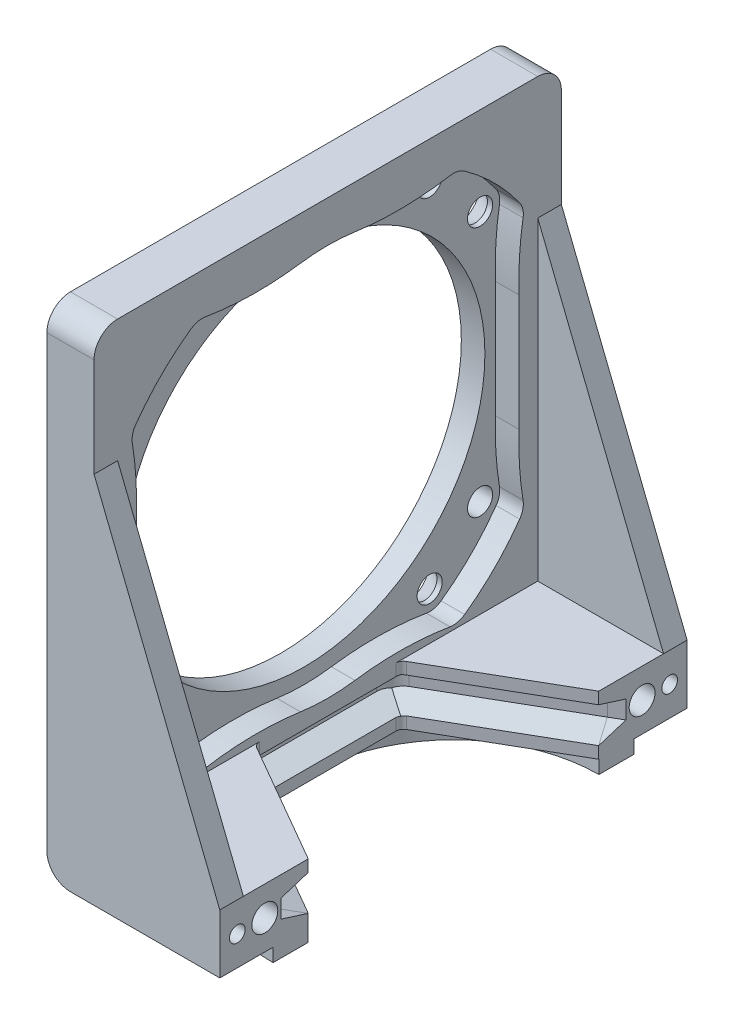
SolidWorks part; units mm, degrees
material "6061 合金"
ref_plane "前视基准面" through (0, 0, 0) normal (0, 0, 1) x (1, 0, 0)
ref_plane "上视基准面" through (0, 0, 0) normal (0, 1, 0) x (1, 0, 0)
ref_plane "右视基准面" through (0, 0, 0) normal (1, 0, 0) x (0, 0, -1)
other "Configuration Table"
sketch "草图1" plane through (0, 0, 0) normal (0, 1, 0) x (1, 0, 0)
  line L0 (0, 18.4752) -> (0, 29.7252)
  line L1 (0, 18.4752) -> (-16, 9.2376)
  line L2 (-16, 9.2376) -> (-16, -9.2376)
  line L3 (-16, -9.2376) -> (0, -18.4752)
  line L4 (0, -18.4752) -> (16, -9.2376) construction
  line L5 (16, -9.2376) -> (16, 9.2376) construction
  line L6 (16, 9.2376) -> (0, 18.4752) construction
  line L7 (0, 29.7252) -> (-22, 29.7252)
  line L8 (-22, 29.7252) -> (-22, -29.7252)
  line L9 (-22, -29.7252) -> (0, -29.7252)
  line L10 (0, -29.7252) -> (0, -18.4752)
  circle A0 centre (0, 0) radius 16 construction
  dimension "D1" = 32
  dimension "D2" = 11.25
  dimension "D3" = 11.25
  dimension "D4" = 6
extrude "凸台-拉伸1" add sketch "草图1" along normal blind 7.5
ref_plane "基准面3" through (12.8714, 0, 7.4313) normal (0.866, 0, 0.5) x (0, -1, 0)
sketch "草图2" plane through (-16.7286, 0, 58.7) normal (-0.866, 0, -0.5) x (-0.5, 0, 0.866)
  line L0 (-33.4573, 3.75) -> (-84.9428, 3.75) construction
  line L1 (-33.4573, 7.5) -> (-33.4573, 0) construction
  line L2 (-84.9428, 7.5) -> (-84.9428, 0) construction
  line L8 (-43.2, 1.5) -> (-43.2, 6)
  line L9 (-43.2, 6) -> (-40.2, 4.9081)
  line L10 (-40.2, 4.9081) -> (-40.2, 2.5919)
  line L11 (-43.2, 1.5) -> (-40.2, 2.5919)
  line L12 (-43.2, 7.5) -> (-43.2, 0) construction
  point P11 (-40.2, 3.75)
  point P12 (-43.2, 3.75)
  dimension "D1" = 4.5
  dimension "D2" = 3
  dimension "D3" = 20
ref_plane "基准面1" through (0, 3.75, 0) normal (0, 1, 0) x (1, 0, 0)
sketch "草图3" plane through (0, 3.75, 0) normal (0, 1, 0) x (1, 0, 0)
  line L0 (0, -18.4752) -> (-16, -9.2376) construction
  line L1 (-16, 9.2376) -> (0, 18.4752) construction
  line L2 (-16, -9.2376) -> (-16, 9.2376) construction
  line L3 (0, -18.4752) -> (-16, -9.2376)
  line L4 (-16, 9.2376) -> (0, 18.4752)
  line L5 (-16, -9.2376) -> (-16, 9.2376)
  line L6 (0, 18.4752) -> (14.6817, 26.9517)
  line L7 (0, -18.4752) -> (14.7818, -27.0095)
sweep "切除-扫描1" cut profiles "草图2" path "草图3"
fillet "圆角1" radius 3 2 edges at (-19, 3.75, -10.9697) (-19, 3.75, 10.9697)
fillet "圆角2" radius 1 4 edges at (-16, 0.75, -9.2376) (-16, 6.75, -9.2376) (-16, 0.75, 9.2376) (-16, 6.75, 9.2376)
sketch "草图4" plane through (0, 7.5, 0) normal (0, 1, 0) x (1, 0, 0)
  line L0 (-22, -29.7252) -> (0, -29.7252) construction
  line L1 (-22, 29.7252) -> (-19, 29.7252)
  line L2 (-22, 29.7252) -> (-22, -29.7252)
  line L3 (-22, -29.7252) -> (-19, -29.7252)
  line L4 (-19, 29.7252) -> (-19, -29.7252)
  dimension "D1" = 3
extrude "凸台-拉伸2" add sketch "草图4" along normal blind 55.6
sketch "草图5" plane through (-22, 0, 0) normal (-1, 0, 0) x (0, 0, 1)
  line L0 (-29.7252, 0) -> (29.7252, 0) construction
  line L1 (-27.5, 32.9) -> (0, 32.9) construction
  line L2 (-22.3882, 48.8693) -> (0, 32.9) construction
  line L3 (-15.9693, 55.2882) -> (0, 32.9) construction
  circle A0 centre (0, 32.9) radius 27.5 construction
  circle A1 centre (-22.3882, 48.8693) radius 1.6
  circle A2 centre (-15.9693, 55.2882) radius 1.6
  circle A3 centre (15.9693, 55.2882) radius 1.6
  circle A4 centre (22.3882, 48.8693) radius 1.6
  circle A5 centre (22.3882, 16.9307) radius 1.6
  circle A6 centre (15.9693, 10.5118) radius 1.6
  circle A7 centre (-15.9693, 10.5118) radius 1.6
  circle A8 centre (-22.3882, 16.9307) radius 1.6
  circle A9 centre (0, 32.9) radius 23
  point P25 (0, 32.9)
  dimension "D2" = 55
  dimension "D5" = 3.2
  dimension "D6" = 3.2
  dimension "D8" = 46
  dimension "D1" = 32.9
  dimension "D3" = 35.5
  dimension "D4" = 19
  dimension "D7" = 4
extrude "切除-拉伸1" cut sketch "草图5" against normal blind 55.6
ref_axis "基准轴1" through (-19, 10.5118, -15.9693) along (-1, 0, 0)
ref_plane "基准面2" through (0, 0, -15.9693) normal (0, 0, 1) x (-1, 0, 0)
sketch "草图6" plane through (0, 0, -15.9693) normal (0, 0, 1) x (-1, 0, 0)
  line L0 (22, -10.5118) -> (22, -7.5118)
  line L1 (19, -10.5118) -> (22, -10.5118) construction
  line L2 (22, -7.5118) -> (19.5, -9.0118)
  line L3 (19.5, -9.0118) -> (19.5, -10.5118)
  line L5 (22, -63.1) -> (22, 0) construction
  line L6 (19.5, -10.5118) -> (22, -10.5118)
  dimension "D1" = 3
  dimension "D2" = 1.5
  dimension "D3" = 2.5
revolve "切除-旋转1" cut sketch "草图6" angle 360 about axis through (-19, 10.5118, -15.9693) along (-1, 0, 0)
pattern_circular "阵列(圆周)1" count 4 every 90 about axis through (0, 32.9, 0) along (1, 0, 0) of "切除-旋转1"
sketch "草图7" plane through (-19, 0, 0) normal (1, 0, 0) x (0, 0, -1)
  line L0 (24.348, 25.4) -> (24.3562, 40.2) construction
  line L1 (-24.348, 40.4) -> (-24.3562, 25.6) construction
  line L2 (24.348, 25.4) -> (24.3562, 40.2)
  line L3 (-24.348, 40.4) -> (-24.3562, 25.6)
  line L4 (-29.7252, 7.5) -> (29.7252, 7.5)
  line L5 (29.7252, 7.5) -> (29.7252, 63.1)
  line L6 (29.7252, 63.1) -> (-29.7252, 63.1)
  line L7 (-29.7252, 63.1) -> (-29.7252, 7.5)
  line L8 (-29.7252, 7.5) -> (29.7252, 7.5)
  line L9 (29.7252, 7.5) -> (29.7252, 63.1)
  line L10 (29.7252, 63.1) -> (-29.7252, 63.1)
  line L11 (-29.7252, 63.1) -> (-29.7252, 7.5)
  arc A0 (15.5614, 8.0453) -> (17.4211, 8.4765) centre (15.9693, 10.5118) ccw construction
  arc A1 (24.4235, 15.4789) -> (24.8547, 17.3386) centre (22.3882, 16.9307) ccw construction
  arc A2 (17.4211, 8.4765) -> (24.4235, 15.4789) centre (0, 32.9) ccw construction
  arc A3 (24.3302, 22.9) -> (24.8547, 17.3386) centre (64.3186, 23.8655) ccw construction
  arc A4 (24.348, 25.4) -> (24.3302, 22.9) centre (64.3186, 23.8655) ccw construction
  arc A5 (24.3302, 42.9) -> (24.3562, 40.2) centre (64.3186, 41.9345) ccw construction
  arc A6 (24.8547, 48.4614) -> (24.3302, 42.9) centre (64.3186, 41.9345) ccw construction
  arc A7 (24.8547, 48.4614) -> (24.4235, 50.3211) centre (22.3882, 48.8693) ccw construction
  arc A8 (24.4235, 50.3211) -> (17.4211, 57.3235) centre (0, 32.9) ccw construction
  arc A9 (17.4211, 57.3235) -> (15.5614, 57.7547) centre (15.9693, 55.2882) ccw construction
  arc A10 (3.4705, 57.6074) -> (15.5614, 57.7547) centre (9.0345, 97.2186) ccw construction
  arc A11 (15.5614, 8.0453) -> (3.4705, 8.1926) centre (9.0345, -31.4186) ccw construction
  arc A12 (-3.4705, 8.1926) -> (3.4705, 8.1926) centre (0, 32.9) ccw construction
  arc A13 (-3.4705, 8.1926) -> (-15.5614, 8.0453) centre (-9.0345, -31.4186) ccw construction
  arc A14 (-17.4211, 8.4765) -> (-15.5614, 8.0453) centre (-15.9693, 10.5118) ccw construction
  arc A15 (-24.4235, 15.4789) -> (-17.4211, 8.4765) centre (0, 32.9) ccw construction
  arc A16 (-24.8547, 17.3386) -> (-24.4235, 15.4789) centre (-22.3882, 16.9307) ccw construction
  arc A17 (-24.3302, 22.9) -> (-24.3562, 25.6) centre (-64.3186, 23.8655) ccw construction
  arc A18 (-24.8547, 17.3386) -> (-24.3302, 22.9) centre (-64.3186, 23.8655) ccw construction
  arc A19 (3.4705, 57.6074) -> (-3.4705, 57.6074) centre (0, 32.9) ccw construction
  arc A20 (-15.5614, 57.7547) -> (-3.4705, 57.6074) centre (-9.0345, 97.2186) ccw construction
  arc A21 (-15.5614, 57.7547) -> (-17.4211, 57.3235) centre (-15.9693, 55.2882) ccw construction
  arc A22 (-24.4235, 50.3211) -> (-24.8547, 48.4614) centre (-22.3882, 48.8693) ccw construction
  arc A23 (-17.4211, 57.3235) -> (-24.4235, 50.3211) centre (0, 32.9) ccw construction
  arc A24 (-24.3302, 42.9) -> (-24.8547, 48.4614) centre (-64.3186, 41.9345) ccw construction
  arc A25 (-24.348, 40.4) -> (-24.3302, 42.9) centre (-64.3186, 41.9345) ccw construction
  arc A26 (15.5614, 8.0453) -> (17.4211, 8.4765) centre (15.9693, 10.5118) ccw
  arc A27 (24.4235, 15.4789) -> (24.8547, 17.3386) centre (22.3882, 16.9307) ccw
  arc A28 (17.4211, 8.4765) -> (24.4235, 15.4789) centre (0, 32.9) ccw
  arc A29 (24.3302, 22.9) -> (24.8547, 17.3386) centre (64.3186, 23.8655) ccw
  arc A30 (24.348, 25.4) -> (24.3302, 22.9) centre (64.3186, 23.8655) ccw
  arc A31 (24.3302, 42.9) -> (24.3562, 40.2) centre (64.3186, 41.9345) ccw
  arc A32 (24.8547, 48.4614) -> (24.3302, 42.9) centre (64.3186, 41.9345) ccw
  arc A33 (24.8547, 48.4614) -> (24.4235, 50.3211) centre (22.3882, 48.8693) ccw
  arc A34 (24.4235, 50.3211) -> (17.4211, 57.3235) centre (0, 32.9) ccw
  arc A35 (17.4211, 57.3235) -> (15.5614, 57.7547) centre (15.9693, 55.2882) ccw
  arc A36 (3.4705, 57.6074) -> (15.5614, 57.7547) centre (9.0345, 97.2186) ccw
  arc A37 (15.5614, 8.0453) -> (3.4705, 8.1926) centre (9.0345, -31.4186) ccw
  arc A38 (-3.4705, 8.1926) -> (3.4705, 8.1926) centre (0, 32.9) ccw
  arc A39 (-3.4705, 8.1926) -> (-15.5614, 8.0453) centre (-9.0345, -31.4186) ccw
  arc A40 (-17.4211, 8.4765) -> (-15.5614, 8.0453) centre (-15.9693, 10.5118) ccw
  arc A41 (-24.4235, 15.4789) -> (-17.4211, 8.4765) centre (0, 32.9) ccw
  arc A42 (-24.8547, 17.3386) -> (-24.4235, 15.4789) centre (-22.3882, 16.9307) ccw
  arc A43 (-24.3302, 22.9) -> (-24.3562, 25.6) centre (-64.3186, 23.8655) ccw
  arc A44 (-24.8547, 17.3386) -> (-24.3302, 22.9) centre (-64.3186, 23.8655) ccw
  arc A45 (3.4705, 57.6074) -> (-3.4705, 57.6074) centre (0, 32.9) ccw
  arc A46 (-15.5614, 57.7547) -> (-3.4705, 57.6074) centre (-9.0345, 97.2186) ccw
  arc A47 (-15.5614, 57.7547) -> (-17.4211, 57.3235) centre (-15.9693, 55.2882) ccw
  arc A48 (-24.4235, 50.3211) -> (-24.8547, 48.4614) centre (-22.3882, 48.8693) ccw
  arc A49 (-17.4211, 57.3235) -> (-24.4235, 50.3211) centre (0, 32.9) ccw
  arc A50 (-24.3302, 42.9) -> (-24.8547, 48.4614) centre (-64.3186, 41.9345) ccw
  arc A51 (-24.348, 40.4) -> (-24.3302, 42.9) centre (-64.3186, 41.9345) ccw
  dimension "D1" = 0
extrude "凸台-拉伸3" add sketch "草图7" along normal blind 3
sketch "草图8" plane through (0, 0, 0) normal (1, 0, 0) x (0, 0, -1)
  line L0 (-29.7252, 0) -> (-18.4752, 0) construction
  line L1 (-29.7252, 7.5) -> (-26.7252, 7.5)
  line L2 (-29.7252, 7.5) -> (-29.7252, 0)
  line L3 (-29.7252, 0) -> (-26.7252, 0)
  line L4 (-26.7252, 7.5) -> (-26.7252, 0)
  line L5 (18.4752, 0) -> (29.7252, 0) construction
  line L6 (29.7252, 7.5) -> (26.7252, 7.5)
  line L7 (29.7252, 7.5) -> (29.7252, 0)
  line L8 (29.7252, 0) -> (26.7252, 0)
  line L9 (26.7252, 7.5) -> (26.7252, 0)
  dimension "D1" = 3
  dimension "D2" = 3
extrude "凸台-拉伸4" add sketch "草图8" along normal blind 15
sketch "草图9" plane through (0, 0, 29.7252) normal (0, 0, 1) x (1, 0, 0)
  line L0 (-16, 51.1) -> (13, 7.5)
  line L1 (13, 7.5) -> (-16, 7.5)
  line L2 (-16, 7.5) -> (-16, 51.1)
  line L3 (-16, 63.1) -> (-16, 7.5) construction
  line L4 (-22, 63.1) -> (-16, 63.1) construction
  line L5 (-16, 7.5) -> (15, 7.5) construction
  line L6 (15, 7.5) -> (15, 0) construction
  dimension "D1" = 12
  dimension "D2" = 2
extrude "凸台-拉伸5" add sketch "草图9" against normal blind 3
sketch "草图10" plane through (0, 0, -29.7252) normal (0, 0, -1) x (-1, 0, 0)
  line L3 (16, 7.5) -> (16, 51.1)
  line L4 (16, 51.1) -> (-13, 7.5)
  line L5 (-13, 7.5) -> (-15, 7.5)
  line L6 (16, 7.5) -> (16, 51.1)
  line L7 (16, 51.1) -> (-13, 7.5)
  line L8 (-13, 7.5) -> (-15, 7.5)
  line L13 (0, 0) -> (0, 7.5)
  line L14 (0, 0) -> (0, 7.5)
  line L15 (0, 7.5) -> (16, 7.5)
  line L16 (0, 7.5) -> (16, 7.5)
  line L17 (-15, 7.5) -> (-15, 0)
  line L18 (-15, 7.5) -> (-15, 0)
  line L19 (-15, 0) -> (0, 0)
  line L20 (-15, 0) -> (0, 0)
  dimension "D1" = 0
extrude "凸台-拉伸6" add sketch "草图10" against normal blind 3
sketch "草图12" plane through (0, 0, 0) normal (1, 0, 0) x (0, 0, -1)
  line L0 (12.1, 3.75) -> (-12.1, 3.75) construction
  line L1 (0, 0) -> (0, 6) construction
  line L2 (8.6603, 6) -> (-8.6603, 6) construction
  point P0 (-24, 3.75)
  point P4 (24, 3.75)
  dimension "D1" = 48
hole_wizard "M4 螺纹孔1" positions "草图12" profile "草图13" tap size "M4" standard "GB"
sketch "草图13" plane through (0, 3.75, 24) normal (0, 1, 0) x (0, 0, -1)
  line L0 (0, 0) -> (0, 6.4914)
  line L1 (0, 6.4914) -> (1.65, 5.5)
  line L2 (1.65, 5.5) -> (1.65, 0)
  line L5 (1.65, 0) -> (0, 0)
  line L10 (0, 6.4914) -> (-1.65, 5.5) construction
  line L11 (0, -6.35) -> (0, 107.95) construction
  dimension "螺纹孔钻头直径" = 3.3
  dimension "螺纹孔钻头深度" = 5.5
  dimension "导头角度" = 118
cosmetic thread "孔螺蚊线1" parameters "D1"=4, "D2"=4
cosmetic thread "孔螺蚊线2" parameters "D1"=4, "D2"=4
sketch "草图14" plane through (15, 0, 0) normal (1, 0, 0) x (0, 0, -1)
  line L0 (-28.2252, 7.5) -> (-28.2252, 0) construction
  line L1 (-26.7252, 7.5) -> (-29.7252, 7.5) construction
  line L2 (-29.7252, 0) -> (-26.7252, 0) construction
  line L3 (-29.7252, 3.75) -> (29.7252, 3.75) construction
  line L4 (-29.7252, 7.5) -> (-29.7252, 0) construction
  line L5 (29.7252, 0) -> (29.7252, 7.5) construction
  line L6 (0, 0) -> (0, 6) construction
  line L7 (8.6603, 6) -> (-8.6603, 6) construction
  line L8 (-28.2252, 5.75) -> (-28.2252, 1.75) construction
  line L9 (-27.4752, 5.75) -> (-27.4752, 1.75)
  line L10 (-28.9752, 5.75) -> (-28.9752, 1.75)
  line L11 (28.2252, 5.75) -> (28.2252, 1.75) construction
  line L12 (27.4752, 5.75) -> (27.4752, 1.75)
  line L13 (28.9752, 5.75) -> (28.9752, 1.75)
  arc A2 (-27.4752, 5.75) -> (-28.9752, 5.75) centre (-28.2252, 5.75) ccw
  arc A3 (-28.9752, 1.75) -> (-27.4752, 1.75) centre (-28.2252, 1.75) ccw
  arc A4 (27.4752, 5.75) -> (28.9752, 5.75) centre (28.2252, 5.75) cw
  arc A5 (28.9752, 1.75) -> (27.4752, 1.75) centre (28.2252, 1.75) cw
  point P19 (-28.2252, 3.75)
  point P24 (0, 0)
  point P27 (28.2252, 3.75)
  dimension "D1" = 1.5
  dimension "D2" = 4
extrude "切除-拉伸2" cut sketch "草图14" against normal blind 5.2
sketch "草图17" plane through (0, 0, 0) normal (0, -1, 0) x (1, 0, 0)
  line L0 (0, 26.7252) -> (0, 18.4752) construction
  line L1 (0, 18.4752) -> (-15.5, 9.5263) construction
  line L2 (-16, 8.6603) -> (-16, -8.6603) construction
  line L3 (0, -18.4752) -> (0, -26.7252) construction
  line L4 (-15.5, -9.5263) -> (0, -18.4752) construction
  line L5 (0, -18.4752) -> (0, -26.7252)
  line L6 (-15.5, -9.5263) -> (0, -18.4752)
  line L7 (-16, 8.6603) -> (-16, -8.6603)
  line L8 (0, 18.4752) -> (-15.5, 9.5263)
  line L9 (0, 26.7252) -> (0, 18.4752)
  circle A0 centre (0, 0) radius 22.95
  arc A1 (-16, -8.6603) -> (-15.5, -9.5263) centre (-15, -8.6603) ccw construction
  arc A2 (-15.5, 9.5263) -> (-16, 8.6603) centre (-15, 8.6603) ccw construction
  arc A3 (-16, -8.6603) -> (-15.5, -9.5263) centre (-15, -8.6603) ccw
  arc A4 (-15.5, 9.5263) -> (-16, 8.6603) centre (-15, 8.6603) ccw
  line M2 (0, -18.4752) -> (-15.5, -9.5263)
  arc M3 (-15.5, -9.5263) -> (-16, -8.6603) centre (-15, -8.6603) cw
  line M4 (-16, -8.6603) -> (-16, 8.6603)
  arc M5 (-16, 8.6603) -> (-15.5, 9.5263) centre (-15, 8.6603) cw
  line M6 (-15.5, 9.5263) -> (0, 18.4752)
  line M7 (0, 18.4752) -> (0, 26.7252)
  line M11 (-22, 29.7252) -> (-22, -29.7252)
  dimension "D1" = 45.9
extrude "凸台-拉伸7" add sketch "草图17" along normal blind 1.7 contours A0 L5 M7 M11 M2 M3 M4 M5 M6
fillet "圆角5" radius 3 3 edges at (-22, 0, -18.13) (-19, 63.1, 29.7252) (-19, 63.1, -29.7252)
sketch "草图18" plane through (0, -1.7, 0) normal (0, -1, 0) x (1, 0, 0)
  circle A0 centre (0, 0) radius 18.5
  dimension "D1" = 37
extrude "切除-拉伸3" cut sketch "草图18" against normal up to surface (1.7 mm away) up to face at (-1.5423, 0, -25.1811)
sketch "草图19" plane through (0, 0, 29.7252) normal (0, 0, 1) x (1, 0, 0)
  line L0 (-16, 51.1) -> (-16, 0)
  line L1 (-19, 0) -> (0, 0) construction
  line L2 (15, 7.5) -> (-22, 7.5)
  line L3 (-22, 60.1) -> (-22, 3) construction
  line L4 (-16, 7.5) -> (-1.5, 29.3)
  line L5 (13, 7.5) -> (-16, 51.1) construction
  line L6 (-16, 51.1) -> (13, 7.5)
  line L7 (-18.4979, 49.4385) -> (10.5021, 5.8385)
  line L8 (-14.751, 6.6693) -> (-0.251, 28.4693)
  line L9 (-17.249, 8.3307) -> (-2.749, 30.1307)
  dimension "D1" = 3
  dimension "D2" = 1.5
  dimension "D3" = 1.5
chamfer "倒角2" distance 0.5 angle 45 4 edges at (15, 3.75, -29.7252) (15, 3.75, -26.7252) (15, 3.75, 26.7252) (15, 3.75, 29.7252)
sketch "草图21" plane through (0, 0, 26.7252) normal (0, 0, -1) x (-1, 0, 0)
  line L0 (-14.5, 0) -> (-15, 0)
  line L1 (-15, 0) -> (-15, 7.5)
  line L2 (-15, 7.5) -> (-14.5, 7.5)
  line L7 (-13, 7.5) -> (-14.5, 7.5)
  line L8 (-14.5, 7.5) -> (-14.5, 0)
  line L9 (-14.5, 0) -> (0, 0)
  line L10 (0, 0) -> (0, 7.5)
  line L11 (0, 7.5) -> (16, 7.5)
  line L12 (16, 7.5) -> (16, 51.1)
  line L13 (16, 51.1) -> (-13, 7.5)
  line L14 (-13, 7.5) -> (-14.5, 7.5)
  line L16 (-14.5, 0) -> (0, 0)
  line L18 (0, 7.5) -> (16, 7.5)
  line L19 (16, 7.5) -> (16, 51.1)
  line L20 (16, 51.1) -> (-13, 7.5)
  line L24 (0, 0) -> (0, 7.5)
  dimension "D1" = 0
extrude "切除-拉伸5" cut sketch "草图21" against normal through all and the other way through all
sketch "草图22" plane through (0, 0, 29.7252) normal (0, 0, 1) x (1, 0, 0)
  line L0 (0, 7.5) -> (-16, 47.5)
  line L1 (-16, 60.1) -> (-16, 7.5) construction
  line L2 (-16, 47.5) -> (-16, 7.5)
  line L3 (-16, 7.5) -> (0, 7.5)
  dimension "D1" = 40
extrude "凸台-拉伸8" add sketch "草图22" against normal blind 3
sketch "草图23" plane through (0, 0, -29.7252) normal (0, 0, -1) x (-1, 0, 0)
  line L3 (0, 7.5) -> (16, 7.5)
  line L4 (16, 7.5) -> (16, 47.5)
  line L5 (16, 47.5) -> (0, 7.5)
  line L6 (0, 7.5) -> (16, 7.5)
  line L7 (16, 7.5) -> (16, 47.5)
  line L8 (16, 47.5) -> (0, 7.5)
  dimension "D1" = 0
extrude "凸台-拉伸9" add sketch "草图23" against normal blind 3
sketch "草图24" plane through (0, 0, 0) normal (1, 0, 0) x (0, 0, -1)
  line L0 (-29.7252, 3.75) -> (29.7252, 3.75) construction
  line L1 (-29.7252, 0) -> (-29.7252, 7.5) construction
  line L2 (29.7252, 0) -> (29.7252, 7.5) construction
  line L3 (0, 0) -> (0, 7.95) construction
  arc A0 (-3.4705, 8.1926) -> (3.4705, 8.1926) centre (0, 32.9) ccw construction
  circle A1 centre (-27.5, 3.75) radius 1
  circle A2 centre (27.5, 3.75) radius 1
  dimension "D1" = 2
  dimension "D2" = 55
extrude "切除-拉伸6" cut sketch "草图24" against normal blind 3.2
